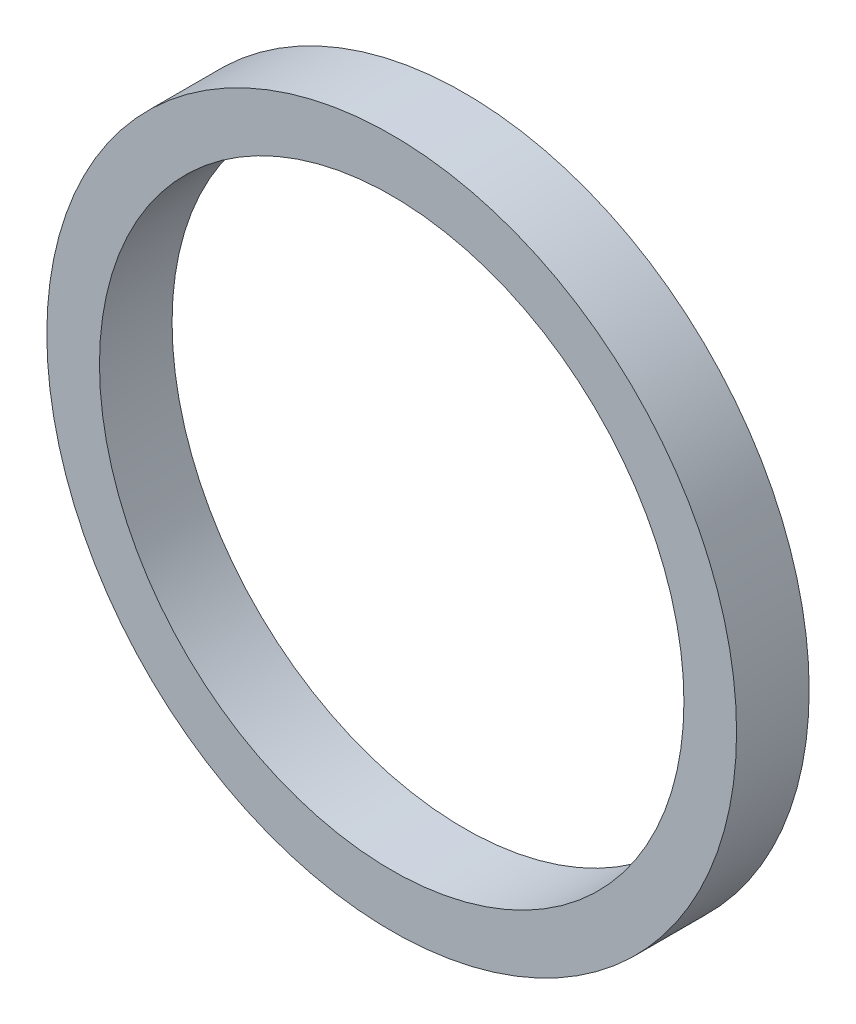
SolidWorks part; units mm, degrees
material "7075-T6 (SN)"
ref_plane "Front Plane" through (0, 0, 0) normal (0, 0, 1) x (1, 0, 0)
ref_plane "Top Plane" through (0, 0, 0) normal (0, 1, 0) x (1, 0, 0)
ref_plane "Right Plane" through (0, 0, 0) normal (1, 0, 0) x (0, 0, -1)
sketch "Sketch1" plane through (0, 0, 0) normal (0, 0, 1) x (1, 0, 0)
  circle A0 centre (0, 0) radius 9.5
  circle A1 centre (0, 0) radius 8.05
  dimension "D1" = 19
  dimension "D2" = 16.1
extrude "Boss-Extrude1" add sketch "Sketch1" along normal blind 2
